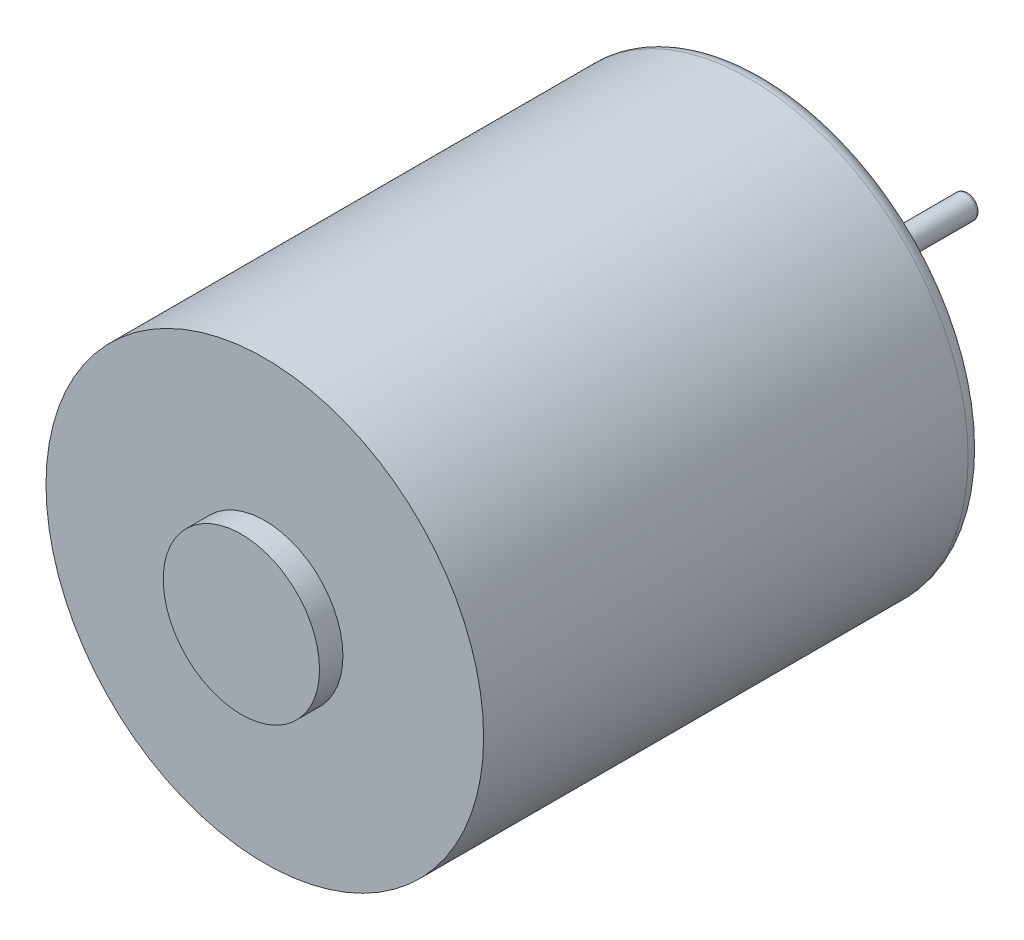
SolidWorks part; units mm, degrees
ref_plane "Front Plane" through (0, 0, 0) normal (0, 0, 1) x (1, 0, 0)
ref_plane "Top Plane" through (0, 0, 0) normal (0, 1, 0) x (1, 0, 0)
ref_plane "Right Plane" through (0, 0, 0) normal (1, 0, 0) x (0, 0, -1)
sketch "Sketch1" plane through (0, 0, 0) normal (0, 0, 1) x (1, 0, 0)
  circle A0 centre (0, 0) radius 14
  dimension "D1" = 28
extrude "Boss-Extrude1" add sketch "Sketch1" along normal blind 32
sketch "Sketch2" plane through (0, 0, 32) normal (0, 0, 1) x (1, 0, 0)
  circle A0 centre (0, 0) radius 5
  dimension "D1" = 10
extrude "Boss-Extrude2" add sketch "Sketch2" along normal blind 1.5
sketch "Sketch3" plane through (0, 0, 0) normal (0, 0, -1) x (-1, 0, 0)
  circle A0 centre (0, 0) radius 5
  dimension "D1" = 10
extrude "Boss-Extrude3" add sketch "Sketch3" along normal blind 3.5
sketch "Sketch4" plane through (0, 0, -3.5) normal (0, 0, -1) x (-1, 0, 0)
  circle A0 centre (0, 0) radius 0.75
  dimension "D1" = 1.5
extrude "Boss-Extrude4" add sketch "Sketch4" along normal blind 9.5
sketch "Sketch5" plane through (0, 0, 0) normal (0, 0, -1) x (-1, 0, 0)
  circle A0 centre (0, 0) radius 8 construction
  circle A1 centre (8, 0) radius 1
  circle A2 centre (-8, 0) radius 1
  dimension "D1" = 16
  dimension "D2" = 2
extrude "Cut-Extrude1" cut sketch "Sketch5" against normal blind 10
fillet "Fillet1" radius 1 1 edges at (14, 0, 0)
fillet "Fillet2" radius 0.2 1 edges at (-0.75, 0, -13)
